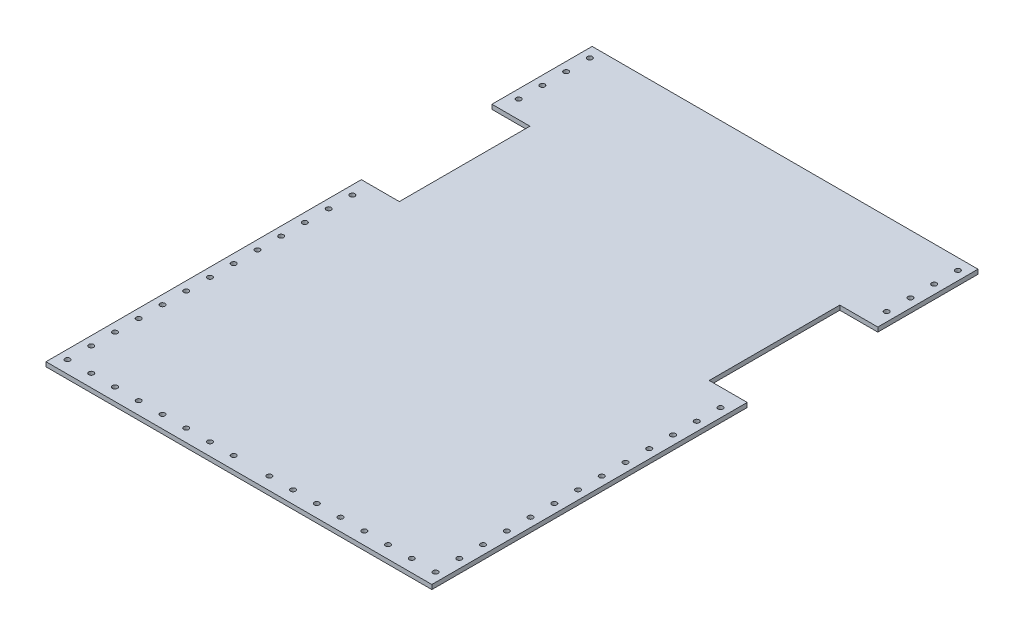
SolidWorks part; units mm, degrees
material "Teak"
ref_plane "Front Plane" through (0, 0, 0) normal (0, 0, 1) x (1, 0, 0)
ref_plane "Top Plane" through (0, 0, 0) normal (0, 1, 0) x (1, 0, 0)
ref_plane "Right Plane" through (0, 0, 0) normal (1, 0, 0) x (0, 0, -1)
sketch "Sketch1" plane through (0, 0, 0) normal (0, 1, 0) x (1, 0, 0)
  line L1 (0, 0) -> (412.75, 0)
  line L2 (0, 0) -> (0, 584.2)
  line L3 (0, 584.2) -> (412.75, 584.2)
  line L4 (412.75, 0) -> (412.75, 584.2)
  dimension "D1" = 584.2
  dimension "D2" = 412.75
extrude "Boss-Extrude1" add sketch "Sketch1" along normal blind 4.7625
sketch "Sketch2" plane through (0, 4.7625, 0) normal (0, 1, 0) x (1, 0, 0)
  line L0 (0, 584.2) -> (0, 0) construction
  line L1 (0, 477.012) -> (40.64, 477.012)
  line L2 (0, 477.012) -> (0, 337.312)
  line L3 (0, 337.312) -> (40.64, 337.312)
  line L4 (40.64, 477.012) -> (40.64, 337.312)
  line L5 (206.375, 0) -> (206.375, 59.5989)
  line L7 (0, 0) -> (412.75, 0) construction
  line L8 (372.11, 477.012) -> (372.11, 337.312)
  line L9 (412.75, 337.312) -> (372.11, 337.312)
  line L10 (412.75, 477.012) -> (412.75, 337.312)
  line L11 (412.75, 477.012) -> (372.11, 477.012)
  line M5 (0, 584.2) -> (0, 0)
  line M7 (412.75, 0) -> (412.75, 584.2)
  dimension "D1" = 139.7
  dimension "D2" = 40.64
extrude "Cut-Extrude1" cut sketch "Sketch2" against normal through all contours L4 L1 L3 M5 | L11 L8 L9 M7
sketch "Sketch3" plane through (0, 4.7625, 0) normal (0, 1, 0) x (1, 0, 0)
  line L0 (0, 337.312) -> (0, 0) construction
  line L1 (0, 0) -> (412.75, 0) construction
  circle A0 centre (9.525, 13.462) radius 2.667
  circle A2 centre (34.925, 13.462) radius 2.667
  circle A4 centre (60.325, 13.462) radius 2.667
  circle A6 centre (85.725, 13.462) radius 2.667
  circle A8 centre (111.125, 13.462) radius 2.667
  circle A10 centre (136.525, 13.462) radius 2.667
  circle A12 centre (161.925, 13.462) radius 2.667
  circle A14 centre (187.325, 13.462) radius 2.667
  circle A17 centre (225.425, 13.462) radius 2.667
  circle A19 centre (250.825, 13.462) radius 2.667
  circle A21 centre (276.225, 13.462) radius 2.667
  circle A23 centre (301.625, 13.462) radius 2.667
  circle A25 centre (327.025, 13.462) radius 2.667
  circle A27 centre (352.425, 13.462) radius 2.667
  circle A29 centre (377.825, 13.462) radius 2.667
  circle A31 centre (403.225, 13.462) radius 2.667
  circle A62 centre (403.225, 38.862) radius 2.667
  circle A93 centre (403.225, 64.262) radius 2.667
  circle A124 centre (403.225, 89.662) radius 2.667
  circle A155 centre (403.225, 115.062) radius 2.667
  circle A186 centre (403.225, 140.462) radius 2.667
  circle A217 centre (403.225, 165.862) radius 2.667
  circle A248 centre (403.225, 191.262) radius 2.667
  circle A279 centre (403.225, 216.662) radius 2.667
  circle A310 centre (403.225, 242.062) radius 2.667
  circle A341 centre (403.225, 267.462) radius 2.667
  circle A372 centre (403.225, 292.862) radius 2.667
  circle A403 centre (403.225, 318.262) radius 2.667
  circle A434 centre (403.225, 343.662) radius 2.667
  circle A465 centre (403.225, 369.062) radius 2.667
  circle A496 centre (403.225, 394.462) radius 2.667
  circle A527 centre (403.225, 419.862) radius 2.667
  circle A558 centre (403.225, 445.262) radius 2.667
  circle A589 centre (403.225, 470.662) radius 2.667
  circle A620 centre (403.225, 496.062) radius 2.667
  circle A651 centre (403.225, 521.462) radius 2.667
  circle A682 centre (403.225, 546.862) radius 2.667
  circle A713 centre (403.225, 572.262) radius 2.667
  circle A714 centre (9.525, 38.862) radius 2.667
  circle A715 centre (9.525, 64.262) radius 2.667
  circle A716 centre (9.525, 89.662) radius 2.667
  circle A717 centre (9.525, 115.062) radius 2.667
  circle A718 centre (9.525, 140.462) radius 2.667
  circle A719 centre (9.525, 165.862) radius 2.667
  circle A720 centre (9.525, 191.262) radius 2.667
  circle A721 centre (9.525, 216.662) radius 2.667
  circle A722 centre (9.525, 242.062) radius 2.667
  circle A723 centre (9.525, 267.462) radius 2.667
  circle A724 centre (9.525, 292.862) radius 2.667
  circle A725 centre (9.525, 318.262) radius 2.667
  circle A726 centre (9.525, 343.662) radius 2.667
  circle A727 centre (9.525, 369.062) radius 2.667
  circle A728 centre (9.525, 394.462) radius 2.667
  circle A729 centre (9.525, 419.862) radius 2.667
  circle A730 centre (9.525, 445.262) radius 2.667
  circle A731 centre (9.525, 470.662) radius 2.667
  circle A732 centre (9.525, 496.062) radius 2.667
  circle A733 centre (9.525, 521.462) radius 2.667
  circle A734 centre (9.525, 546.862) radius 2.667
  circle A735 centre (9.525, 572.262) radius 2.667
  circle A736 centre (34.925, 38.862) radius 2.667 [skipped]
  circle A737 centre (47.625, 38.862) radius 2.667 [skipped]
  circle A738 centre (60.325, 38.862) radius 2.667 [skipped]
  circle A739 centre (73.025, 38.862) radius 2.667 [skipped]
  circle A740 centre (85.725, 38.862) radius 2.667 [skipped]
  circle A741 centre (98.425, 38.862) radius 2.667 [skipped]
  circle A742 centre (111.125, 38.862) radius 2.667 [skipped]
  circle A743 centre (123.825, 38.862) radius 2.667 [skipped]
  circle A744 centre (136.525, 38.862) radius 2.667 [skipped]
  circle A745 centre (149.225, 38.862) radius 2.667 [skipped]
  circle A746 centre (161.925, 38.862) radius 2.667 [skipped]
  circle A747 centre (174.625, 38.862) radius 2.667 [skipped]
  circle A748 centre (187.325, 38.862) radius 2.667 [skipped]
  circle A749 centre (200.025, 38.862) radius 2.667 [skipped]
  circle A750 centre (212.725, 38.862) radius 2.667 [skipped]
  circle A751 centre (225.425, 38.862) radius 2.667 [skipped]
  circle A752 centre (238.125, 38.862) radius 2.667 [skipped]
  circle A753 centre (250.825, 38.862) radius 2.667 [skipped]
  circle A754 centre (263.525, 38.862) radius 2.667 [skipped]
  circle A755 centre (276.225, 38.862) radius 2.667 [skipped]
  circle A756 centre (288.925, 38.862) radius 2.667 [skipped]
  circle A757 centre (301.625, 38.862) radius 2.667 [skipped]
  circle A758 centre (314.325, 38.862) radius 2.667 [skipped]
  circle A759 centre (327.025, 38.862) radius 2.667 [skipped]
  circle A760 centre (339.725, 38.862) radius 2.667 [skipped]
  circle A761 centre (352.425, 38.862) radius 2.667 [skipped]
  circle A762 centre (365.125, 38.862) radius 2.667 [skipped]
  circle A763 centre (377.825, 38.862) radius 2.667 [skipped]
  circle A764 centre (390.525, 38.862) radius 2.667 [skipped]
  circle A765 centre (34.925, 64.262) radius 2.667 [skipped]
  circle A766 centre (47.625, 64.262) radius 2.667 [skipped]
  circle A767 centre (60.325, 64.262) radius 2.667 [skipped]
  circle A768 centre (73.025, 64.262) radius 2.667 [skipped]
  circle A769 centre (85.725, 64.262) radius 2.667 [skipped]
  circle A770 centre (98.425, 64.262) radius 2.667 [skipped]
  circle A771 centre (111.125, 64.262) radius 2.667 [skipped]
  circle A772 centre (123.825, 64.262) radius 2.667 [skipped]
  circle A773 centre (136.525, 64.262) radius 2.667 [skipped]
  circle A774 centre (149.225, 64.262) radius 2.667 [skipped]
  circle A775 centre (161.925, 64.262) radius 2.667 [skipped]
  circle A776 centre (174.625, 64.262) radius 2.667 [skipped]
  circle A777 centre (187.325, 64.262) radius 2.667 [skipped]
  circle A778 centre (200.025, 64.262) radius 2.667 [skipped]
  circle A779 centre (212.725, 64.262) radius 2.667 [skipped]
  circle A780 centre (225.425, 64.262) radius 2.667 [skipped]
  circle A781 centre (238.125, 64.262) radius 2.667 [skipped]
  circle A782 centre (250.825, 64.262) radius 2.667 [skipped]
  circle A783 centre (263.525, 64.262) radius 2.667 [skipped]
  circle A784 centre (276.225, 64.262) radius 2.667 [skipped]
  circle A785 centre (288.925, 64.262) radius 2.667 [skipped]
  circle A786 centre (301.625, 64.262) radius 2.667 [skipped]
  circle A787 centre (314.325, 64.262) radius 2.667 [skipped]
  circle A788 centre (327.025, 64.262) radius 2.667 [skipped]
  circle A789 centre (339.725, 64.262) radius 2.667 [skipped]
  circle A790 centre (352.425, 64.262) radius 2.667 [skipped]
  circle A791 centre (365.125, 64.262) radius 2.667 [skipped]
  circle A792 centre (377.825, 64.262) radius 2.667 [skipped]
  circle A793 centre (390.525, 64.262) radius 2.667 [skipped]
  circle A794 centre (34.925, 89.662) radius 2.667 [skipped]
  circle A795 centre (47.625, 89.662) radius 2.667 [skipped]
  circle A796 centre (60.325, 89.662) radius 2.667 [skipped]
  circle A797 centre (73.025, 89.662) radius 2.667 [skipped]
  circle A798 centre (85.725, 89.662) radius 2.667 [skipped]
  circle A799 centre (98.425, 89.662) radius 2.667 [skipped]
  circle A800 centre (111.125, 89.662) radius 2.667 [skipped]
  circle A801 centre (123.825, 89.662) radius 2.667 [skipped]
  circle A802 centre (136.525, 89.662) radius 2.667 [skipped]
  circle A803 centre (149.225, 89.662) radius 2.667 [skipped]
  circle A804 centre (161.925, 89.662) radius 2.667 [skipped]
  circle A805 centre (174.625, 89.662) radius 2.667 [skipped]
  circle A806 centre (187.325, 89.662) radius 2.667 [skipped]
  circle A807 centre (200.025, 89.662) radius 2.667 [skipped]
  circle A808 centre (212.725, 89.662) radius 2.667 [skipped]
  circle A809 centre (225.425, 89.662) radius 2.667 [skipped]
  circle A810 centre (238.125, 89.662) radius 2.667 [skipped]
  circle A811 centre (250.825, 89.662) radius 2.667 [skipped]
  circle A812 centre (263.525, 89.662) radius 2.667 [skipped]
  circle A813 centre (276.225, 89.662) radius 2.667 [skipped]
  circle A814 centre (288.925, 89.662) radius 2.667 [skipped]
  circle A815 centre (301.625, 89.662) radius 2.667 [skipped]
  circle A816 centre (314.325, 89.662) radius 2.667 [skipped]
  circle A817 centre (327.025, 89.662) radius 2.667 [skipped]
  circle A818 centre (339.725, 89.662) radius 2.667 [skipped]
  circle A819 centre (352.425, 89.662) radius 2.667 [skipped]
  circle A820 centre (365.125, 89.662) radius 2.667 [skipped]
  circle A821 centre (377.825, 89.662) radius 2.667 [skipped]
  circle A822 centre (390.525, 89.662) radius 2.667 [skipped]
  circle A823 centre (34.925, 115.062) radius 2.667 [skipped]
  circle A824 centre (47.625, 115.062) radius 2.667 [skipped]
  circle A825 centre (60.325, 115.062) radius 2.667 [skipped]
  circle A826 centre (73.025, 115.062) radius 2.667 [skipped]
  circle A827 centre (85.725, 115.062) radius 2.667 [skipped]
  circle A828 centre (98.425, 115.062) radius 2.667 [skipped]
  circle A829 centre (111.125, 115.062) radius 2.667 [skipped]
  circle A830 centre (123.825, 115.062) radius 2.667 [skipped]
  circle A831 centre (136.525, 115.062) radius 2.667 [skipped]
  circle A832 centre (149.225, 115.062) radius 2.667 [skipped]
  circle A833 centre (161.925, 115.062) radius 2.667 [skipped]
  circle A834 centre (174.625, 115.062) radius 2.667 [skipped]
  circle A835 centre (187.325, 115.062) radius 2.667 [skipped]
  circle A836 centre (200.025, 115.062) radius 2.667 [skipped]
  circle A837 centre (212.725, 115.062) radius 2.667 [skipped]
  circle A838 centre (225.425, 115.062) radius 2.667 [skipped]
  circle A839 centre (238.125, 115.062) radius 2.667 [skipped]
  circle A840 centre (250.825, 115.062) radius 2.667 [skipped]
  circle A841 centre (263.525, 115.062) radius 2.667 [skipped]
  circle A842 centre (276.225, 115.062) radius 2.667 [skipped]
  circle A843 centre (288.925, 115.062) radius 2.667 [skipped]
  circle A844 centre (301.625, 115.062) radius 2.667 [skipped]
  circle A845 centre (314.325, 115.062) radius 2.667 [skipped]
  circle A846 centre (327.025, 115.062) radius 2.667 [skipped]
  circle A847 centre (339.725, 115.062) radius 2.667 [skipped]
  circle A848 centre (352.425, 115.062) radius 2.667 [skipped]
  circle A849 centre (365.125, 115.062) radius 2.667 [skipped]
  circle A850 centre (377.825, 115.062) radius 2.667 [skipped]
  circle A851 centre (390.525, 115.062) radius 2.667 [skipped]
  circle A852 centre (34.925, 140.462) radius 2.667 [skipped]
  circle A853 centre (47.625, 140.462) radius 2.667 [skipped]
  circle A854 centre (60.325, 140.462) radius 2.667 [skipped]
  circle A855 centre (73.025, 140.462) radius 2.667 [skipped]
  circle A856 centre (85.725, 140.462) radius 2.667 [skipped]
  circle A857 centre (98.425, 140.462) radius 2.667 [skipped]
  circle A858 centre (111.125, 140.462) radius 2.667 [skipped]
  circle A859 centre (123.825, 140.462) radius 2.667 [skipped]
  circle A860 centre (136.525, 140.462) radius 2.667 [skipped]
  circle A861 centre (149.225, 140.462) radius 2.667 [skipped]
  circle A862 centre (161.925, 140.462) radius 2.667 [skipped]
  circle A863 centre (174.625, 140.462) radius 2.667 [skipped]
  circle A864 centre (187.325, 140.462) radius 2.667 [skipped]
  circle A865 centre (200.025, 140.462) radius 2.667 [skipped]
  circle A866 centre (212.725, 140.462) radius 2.667 [skipped]
  circle A867 centre (225.425, 140.462) radius 2.667 [skipped]
  circle A868 centre (238.125, 140.462) radius 2.667 [skipped]
  circle A869 centre (250.825, 140.462) radius 2.667 [skipped]
  circle A870 centre (263.525, 140.462) radius 2.667 [skipped]
  circle A871 centre (276.225, 140.462) radius 2.667 [skipped]
  circle A872 centre (288.925, 140.462) radius 2.667 [skipped]
  circle A873 centre (301.625, 140.462) radius 2.667 [skipped]
  circle A874 centre (314.325, 140.462) radius 2.667 [skipped]
  circle A875 centre (327.025, 140.462) radius 2.667 [skipped]
  circle A876 centre (339.725, 140.462) radius 2.667 [skipped]
  circle A877 centre (352.425, 140.462) radius 2.667 [skipped]
  circle A878 centre (365.125, 140.462) radius 2.667 [skipped]
  circle A879 centre (377.825, 140.462) radius 2.667 [skipped]
  circle A880 centre (390.525, 140.462) radius 2.667 [skipped]
  circle A881 centre (34.925, 165.862) radius 2.667 [skipped]
  circle A882 centre (47.625, 165.862) radius 2.667 [skipped]
  circle A883 centre (60.325, 165.862) radius 2.667 [skipped]
  circle A884 centre (73.025, 165.862) radius 2.667 [skipped]
  circle A885 centre (85.725, 165.862) radius 2.667 [skipped]
  circle A886 centre (98.425, 165.862) radius 2.667 [skipped]
  circle A887 centre (111.125, 165.862) radius 2.667 [skipped]
  circle A888 centre (123.825, 165.862) radius 2.667 [skipped]
  circle A889 centre (136.525, 165.862) radius 2.667 [skipped]
  circle A890 centre (149.225, 165.862) radius 2.667 [skipped]
  circle A891 centre (161.925, 165.862) radius 2.667 [skipped]
  circle A892 centre (174.625, 165.862) radius 2.667 [skipped]
  circle A893 centre (187.325, 165.862) radius 2.667 [skipped]
  circle A894 centre (200.025, 165.862) radius 2.667 [skipped]
  circle A895 centre (212.725, 165.862) radius 2.667 [skipped]
  circle A896 centre (225.425, 165.862) radius 2.667 [skipped]
  circle A897 centre (238.125, 165.862) radius 2.667 [skipped]
  circle A898 centre (250.825, 165.862) radius 2.667 [skipped]
  circle A899 centre (263.525, 165.862) radius 2.667 [skipped]
  circle A900 centre (276.225, 165.862) radius 2.667 [skipped]
  circle A901 centre (288.925, 165.862) radius 2.667 [skipped]
  circle A902 centre (301.625, 165.862) radius 2.667 [skipped]
  circle A903 centre (314.325, 165.862) radius 2.667 [skipped]
  circle A904 centre (327.025, 165.862) radius 2.667 [skipped]
  circle A905 centre (339.725, 165.862) radius 2.667 [skipped]
  circle A906 centre (352.425, 165.862) radius 2.667 [skipped]
  circle A907 centre (365.125, 165.862) radius 2.667 [skipped]
  circle A908 centre (377.825, 165.862) radius 2.667 [skipped]
  circle A909 centre (390.525, 165.862) radius 2.667 [skipped]
  circle A910 centre (34.925, 191.262) radius 2.667 [skipped]
  circle A911 centre (47.625, 191.262) radius 2.667 [skipped]
  circle A912 centre (60.325, 191.262) radius 2.667 [skipped]
  circle A913 centre (73.025, 191.262) radius 2.667 [skipped]
  circle A914 centre (85.725, 191.262) radius 2.667 [skipped]
  circle A915 centre (98.425, 191.262) radius 2.667 [skipped]
  circle A916 centre (111.125, 191.262) radius 2.667 [skipped]
  circle A917 centre (123.825, 191.262) radius 2.667 [skipped]
  circle A918 centre (136.525, 191.262) radius 2.667 [skipped]
  circle A919 centre (149.225, 191.262) radius 2.667 [skipped]
  circle A920 centre (161.925, 191.262) radius 2.667 [skipped]
  circle A921 centre (174.625, 191.262) radius 2.667 [skipped]
  circle A922 centre (187.325, 191.262) radius 2.667 [skipped]
  circle A923 centre (200.025, 191.262) radius 2.667 [skipped]
  circle A924 centre (212.725, 191.262) radius 2.667 [skipped]
  circle A925 centre (225.425, 191.262) radius 2.667 [skipped]
  circle A926 centre (238.125, 191.262) radius 2.667 [skipped]
  circle A927 centre (250.825, 191.262) radius 2.667 [skipped]
  circle A928 centre (263.525, 191.262) radius 2.667 [skipped]
  circle A929 centre (276.225, 191.262) radius 2.667 [skipped]
  circle A930 centre (288.925, 191.262) radius 2.667 [skipped]
  circle A931 centre (301.625, 191.262) radius 2.667 [skipped]
  circle A932 centre (314.325, 191.262) radius 2.667 [skipped]
  circle A933 centre (327.025, 191.262) radius 2.667 [skipped]
  circle A934 centre (339.725, 191.262) radius 2.667 [skipped]
  circle A935 centre (352.425, 191.262) radius 2.667 [skipped]
  circle A936 centre (365.125, 191.262) radius 2.667 [skipped]
  circle A937 centre (377.825, 191.262) radius 2.667 [skipped]
  circle A938 centre (390.525, 191.262) radius 2.667 [skipped]
  circle A939 centre (34.925, 216.662) radius 2.667 [skipped]
  circle A940 centre (47.625, 216.662) radius 2.667 [skipped]
  circle A941 centre (60.325, 216.662) radius 2.667 [skipped]
  circle A942 centre (73.025, 216.662) radius 2.667 [skipped]
  circle A943 centre (85.725, 216.662) radius 2.667 [skipped]
  circle A944 centre (98.425, 216.662) radius 2.667 [skipped]
  circle A945 centre (111.125, 216.662) radius 2.667 [skipped]
  circle A946 centre (123.825, 216.662) radius 2.667 [skipped]
  circle A947 centre (136.525, 216.662) radius 2.667 [skipped]
  circle A948 centre (149.225, 216.662) radius 2.667 [skipped]
  circle A949 centre (161.925, 216.662) radius 2.667 [skipped]
  circle A950 centre (174.625, 216.662) radius 2.667 [skipped]
  circle A951 centre (187.325, 216.662) radius 2.667 [skipped]
  circle A952 centre (200.025, 216.662) radius 2.667 [skipped]
  circle A953 centre (212.725, 216.662) radius 2.667 [skipped]
  circle A954 centre (225.425, 216.662) radius 2.667 [skipped]
  circle A955 centre (238.125, 216.662) radius 2.667 [skipped]
  circle A956 centre (250.825, 216.662) radius 2.667 [skipped]
  circle A957 centre (263.525, 216.662) radius 2.667 [skipped]
  circle A958 centre (276.225, 216.662) radius 2.667 [skipped]
  circle A959 centre (288.925, 216.662) radius 2.667 [skipped]
  circle A960 centre (301.625, 216.662) radius 2.667 [skipped]
  circle A961 centre (314.325, 216.662) radius 2.667 [skipped]
  circle A962 centre (327.025, 216.662) radius 2.667 [skipped]
  circle A963 centre (339.725, 216.662) radius 2.667 [skipped]
  circle A964 centre (352.425, 216.662) radius 2.667 [skipped]
  circle A965 centre (365.125, 216.662) radius 2.667 [skipped]
  circle A966 centre (377.825, 216.662) radius 2.667 [skipped]
  circle A967 centre (390.525, 216.662) radius 2.667 [skipped]
  circle A968 centre (34.925, 242.062) radius 2.667 [skipped]
  circle A969 centre (47.625, 242.062) radius 2.667 [skipped]
  circle A970 centre (60.325, 242.062) radius 2.667 [skipped]
  circle A971 centre (73.025, 242.062) radius 2.667 [skipped]
  circle A972 centre (85.725, 242.062) radius 2.667 [skipped]
  circle A973 centre (98.425, 242.062) radius 2.667 [skipped]
  circle A974 centre (111.125, 242.062) radius 2.667 [skipped]
  circle A975 centre (123.825, 242.062) radius 2.667 [skipped]
  circle A976 centre (136.525, 242.062) radius 2.667 [skipped]
  circle A977 centre (149.225, 242.062) radius 2.667 [skipped]
  circle A978 centre (161.925, 242.062) radius 2.667 [skipped]
  circle A979 centre (174.625, 242.062) radius 2.667 [skipped]
  circle A980 centre (187.325, 242.062) radius 2.667 [skipped]
  circle A981 centre (200.025, 242.062) radius 2.667 [skipped]
  circle A982 centre (212.725, 242.062) radius 2.667 [skipped]
  circle A983 centre (225.425, 242.062) radius 2.667 [skipped]
  circle A984 centre (238.125, 242.062) radius 2.667 [skipped]
  circle A985 centre (250.825, 242.062) radius 2.667 [skipped]
  circle A986 centre (263.525, 242.062) radius 2.667 [skipped]
  circle A987 centre (276.225, 242.062) radius 2.667 [skipped]
  circle A988 centre (288.925, 242.062) radius 2.667 [skipped]
  circle A989 centre (301.625, 242.062) radius 2.667 [skipped]
  circle A990 centre (314.325, 242.062) radius 2.667 [skipped]
  circle A991 centre (327.025, 242.062) radius 2.667 [skipped]
  circle A992 centre (339.725, 242.062) radius 2.667 [skipped]
  circle A993 centre (352.425, 242.062) radius 2.667 [skipped]
  circle A994 centre (365.125, 242.062) radius 2.667 [skipped]
  circle A995 centre (377.825, 242.062) radius 2.667 [skipped]
  circle A996 centre (390.525, 242.062) radius 2.667 [skipped]
  circle A997 centre (34.925, 267.462) radius 2.667 [skipped]
  circle A998 centre (47.625, 267.462) radius 2.667 [skipped]
  circle A999 centre (60.325, 267.462) radius 2.667 [skipped]
  circle A1000 centre (73.025, 267.462) radius 2.667 [skipped]
  circle A1001 centre (85.725, 267.462) radius 2.667 [skipped]
  circle A1002 centre (98.425, 267.462) radius 2.667 [skipped]
  circle A1003 centre (111.125, 267.462) radius 2.667 [skipped]
  circle A1004 centre (123.825, 267.462) radius 2.667 [skipped]
  circle A1005 centre (136.525, 267.462) radius 2.667 [skipped]
  circle A1006 centre (149.225, 267.462) radius 2.667 [skipped]
  circle A1007 centre (161.925, 267.462) radius 2.667 [skipped]
  circle A1008 centre (174.625, 267.462) radius 2.667 [skipped]
  circle A1009 centre (187.325, 267.462) radius 2.667 [skipped]
  circle A1010 centre (200.025, 267.462) radius 2.667 [skipped]
  circle A1011 centre (212.725, 267.462) radius 2.667 [skipped]
  circle A1012 centre (225.425, 267.462) radius 2.667 [skipped]
  circle A1013 centre (238.125, 267.462) radius 2.667 [skipped]
  circle A1014 centre (250.825, 267.462) radius 2.667 [skipped]
  circle A1015 centre (263.525, 267.462) radius 2.667 [skipped]
  circle A1016 centre (276.225, 267.462) radius 2.667 [skipped]
  circle A1017 centre (288.925, 267.462) radius 2.667 [skipped]
  circle A1018 centre (301.625, 267.462) radius 2.667 [skipped]
  circle A1019 centre (314.325, 267.462) radius 2.667 [skipped]
  circle A1020 centre (327.025, 267.462) radius 2.667 [skipped]
  circle A1021 centre (339.725, 267.462) radius 2.667 [skipped]
  circle A1022 centre (352.425, 267.462) radius 2.667 [skipped]
  circle A1023 centre (365.125, 267.462) radius 2.667 [skipped]
  circle A1024 centre (377.825, 267.462) radius 2.667 [skipped]
  circle A1025 centre (390.525, 267.462) radius 2.667 [skipped]
  circle A1026 centre (34.925, 292.862) radius 2.667 [skipped]
  circle A1027 centre (47.625, 292.862) radius 2.667 [skipped]
  circle A1028 centre (60.325, 292.862) radius 2.667 [skipped]
  circle A1029 centre (73.025, 292.862) radius 2.667 [skipped]
  circle A1030 centre (85.725, 292.862) radius 2.667 [skipped]
  circle A1031 centre (98.425, 292.862) radius 2.667 [skipped]
  circle A1032 centre (111.125, 292.862) radius 2.667 [skipped]
  circle A1033 centre (123.825, 292.862) radius 2.667 [skipped]
  circle A1034 centre (136.525, 292.862) radius 2.667 [skipped]
  circle A1035 centre (149.225, 292.862) radius 2.667 [skipped]
  circle A1036 centre (161.925, 292.862) radius 2.667 [skipped]
  circle A1037 centre (174.625, 292.862) radius 2.667 [skipped]
  circle A1038 centre (187.325, 292.862) radius 2.667 [skipped]
  circle A1039 centre (200.025, 292.862) radius 2.667 [skipped]
  circle A1040 centre (212.725, 292.862) radius 2.667 [skipped]
  circle A1041 centre (225.425, 292.862) radius 2.667 [skipped]
  circle A1042 centre (238.125, 292.862) radius 2.667 [skipped]
  circle A1043 centre (250.825, 292.862) radius 2.667 [skipped]
  circle A1044 centre (263.525, 292.862) radius 2.667 [skipped]
  circle A1045 centre (276.225, 292.862) radius 2.667 [skipped]
  circle A1046 centre (288.925, 292.862) radius 2.667 [skipped]
  circle A1047 centre (301.625, 292.862) radius 2.667 [skipped]
  circle A1048 centre (314.325, 292.862) radius 2.667 [skipped]
  circle A1049 centre (327.025, 292.862) radius 2.667 [skipped]
  circle A1050 centre (339.725, 292.862) radius 2.667 [skipped]
  circle A1051 centre (352.425, 292.862) radius 2.667 [skipped]
  circle A1052 centre (365.125, 292.862) radius 2.667 [skipped]
  circle A1053 centre (377.825, 292.862) radius 2.667 [skipped]
  circle A1054 centre (390.525, 292.862) radius 2.667 [skipped]
  circle A1055 centre (34.925, 318.262) radius 2.667 [skipped]
  circle A1056 centre (47.625, 318.262) radius 2.667 [skipped]
  circle A1057 centre (60.325, 318.262) radius 2.667 [skipped]
  circle A1058 centre (73.025, 318.262) radius 2.667 [skipped]
  circle A1059 centre (85.725, 318.262) radius 2.667 [skipped]
  circle A1060 centre (98.425, 318.262) radius 2.667 [skipped]
  circle A1061 centre (111.125, 318.262) radius 2.667 [skipped]
  circle A1062 centre (123.825, 318.262) radius 2.667 [skipped]
  circle A1063 centre (136.525, 318.262) radius 2.667 [skipped]
  circle A1064 centre (149.225, 318.262) radius 2.667 [skipped]
  circle A1065 centre (161.925, 318.262) radius 2.667 [skipped]
  circle A1066 centre (174.625, 318.262) radius 2.667 [skipped]
  circle A1067 centre (187.325, 318.262) radius 2.667 [skipped]
  circle A1068 centre (200.025, 318.262) radius 2.667 [skipped]
  circle A1069 centre (212.725, 318.262) radius 2.667 [skipped]
  circle A1070 centre (225.425, 318.262) radius 2.667 [skipped]
  circle A1071 centre (238.125, 318.262) radius 2.667 [skipped]
  circle A1072 centre (250.825, 318.262) radius 2.667 [skipped]
  circle A1073 centre (263.525, 318.262) radius 2.667 [skipped]
  circle A1074 centre (276.225, 318.262) radius 2.667 [skipped]
  circle A1075 centre (288.925, 318.262) radius 2.667 [skipped]
  circle A1076 centre (301.625, 318.262) radius 2.667 [skipped]
  circle A1077 centre (314.325, 318.262) radius 2.667 [skipped]
  circle A1078 centre (327.025, 318.262) radius 2.667 [skipped]
  circle A1079 centre (339.725, 318.262) radius 2.667 [skipped]
  circle A1080 centre (352.425, 318.262) radius 2.667 [skipped]
  circle A1081 centre (365.125, 318.262) radius 2.667 [skipped]
  circle A1082 centre (377.825, 318.262) radius 2.667 [skipped]
  circle A1083 centre (390.525, 318.262) radius 2.667 [skipped]
  circle A1084 centre (34.925, 343.662) radius 2.667 [skipped]
  circle A1085 centre (47.625, 343.662) radius 2.667 [skipped]
  circle A1086 centre (60.325, 343.662) radius 2.667 [skipped]
  circle A1087 centre (73.025, 343.662) radius 2.667 [skipped]
  circle A1088 centre (85.725, 343.662) radius 2.667 [skipped]
  circle A1089 centre (98.425, 343.662) radius 2.667 [skipped]
  circle A1090 centre (111.125, 343.662) radius 2.667 [skipped]
  circle A1091 centre (123.825, 343.662) radius 2.667 [skipped]
  circle A1092 centre (136.525, 343.662) radius 2.667 [skipped]
  circle A1093 centre (149.225, 343.662) radius 2.667 [skipped]
  circle A1094 centre (161.925, 343.662) radius 2.667 [skipped]
  circle A1095 centre (174.625, 343.662) radius 2.667 [skipped]
  circle A1096 centre (187.325, 343.662) radius 2.667 [skipped]
  circle A1097 centre (200.025, 343.662) radius 2.667 [skipped]
  circle A1098 centre (212.725, 343.662) radius 2.667 [skipped]
  circle A1099 centre (225.425, 343.662) radius 2.667 [skipped]
  circle A1100 centre (238.125, 343.662) radius 2.667 [skipped]
  circle A1101 centre (250.825, 343.662) radius 2.667 [skipped]
  circle A1102 centre (263.525, 343.662) radius 2.667 [skipped]
  circle A1103 centre (276.225, 343.662) radius 2.667 [skipped]
  circle A1104 centre (288.925, 343.662) radius 2.667 [skipped]
  circle A1105 centre (301.625, 343.662) radius 2.667 [skipped]
  circle A1106 centre (314.325, 343.662) radius 2.667 [skipped]
  circle A1107 centre (327.025, 343.662) radius 2.667 [skipped]
  circle A1108 centre (339.725, 343.662) radius 2.667 [skipped]
  circle A1109 centre (352.425, 343.662) radius 2.667 [skipped]
  circle A1110 centre (365.125, 343.662) radius 2.667 [skipped]
  circle A1111 centre (377.825, 343.662) radius 2.667 [skipped]
  circle A1112 centre (390.525, 343.662) radius 2.667 [skipped]
  circle A1113 centre (34.925, 369.062) radius 2.667 [skipped]
  circle A1114 centre (47.625, 369.062) radius 2.667 [skipped]
  circle A1115 centre (60.325, 369.062) radius 2.667 [skipped]
  circle A1116 centre (73.025, 369.062) radius 2.667 [skipped]
  circle A1117 centre (85.725, 369.062) radius 2.667 [skipped]
  circle A1118 centre (98.425, 369.062) radius 2.667 [skipped]
  circle A1119 centre (111.125, 369.062) radius 2.667 [skipped]
  circle A1120 centre (123.825, 369.062) radius 2.667 [skipped]
  circle A1121 centre (136.525, 369.062) radius 2.667 [skipped]
  circle A1122 centre (149.225, 369.062) radius 2.667 [skipped]
  circle A1123 centre (161.925, 369.062) radius 2.667 [skipped]
  circle A1124 centre (174.625, 369.062) radius 2.667 [skipped]
  circle A1125 centre (187.325, 369.062) radius 2.667 [skipped]
  circle A1126 centre (200.025, 369.062) radius 2.667 [skipped]
  circle A1127 centre (212.725, 369.062) radius 2.667 [skipped]
  circle A1128 centre (225.425, 369.062) radius 2.667 [skipped]
  circle A1129 centre (238.125, 369.062) radius 2.667 [skipped]
  circle A1130 centre (250.825, 369.062) radius 2.667 [skipped]
  circle A1131 centre (263.525, 369.062) radius 2.667 [skipped]
  circle A1132 centre (276.225, 369.062) radius 2.667 [skipped]
  circle A1133 centre (288.925, 369.062) radius 2.667 [skipped]
  circle A1134 centre (301.625, 369.062) radius 2.667 [skipped]
  circle A1135 centre (314.325, 369.062) radius 2.667 [skipped]
  circle A1136 centre (327.025, 369.062) radius 2.667 [skipped]
  circle A1137 centre (339.725, 369.062) radius 2.667 [skipped]
  circle A1138 centre (352.425, 369.062) radius 2.667 [skipped]
  circle A1139 centre (365.125, 369.062) radius 2.667 [skipped]
  circle A1140 centre (377.825, 369.062) radius 2.667 [skipped]
  circle A1141 centre (390.525, 369.062) radius 2.667 [skipped]
  circle A1142 centre (34.925, 394.462) radius 2.667 [skipped]
  circle A1143 centre (47.625, 394.462) radius 2.667 [skipped]
  circle A1144 centre (60.325, 394.462) radius 2.667 [skipped]
  circle A1145 centre (73.025, 394.462) radius 2.667 [skipped]
  circle A1146 centre (85.725, 394.462) radius 2.667 [skipped]
  circle A1147 centre (98.425, 394.462) radius 2.667 [skipped]
  circle A1148 centre (111.125, 394.462) radius 2.667 [skipped]
  circle A1149 centre (123.825, 394.462) radius 2.667 [skipped]
  circle A1150 centre (136.525, 394.462) radius 2.667 [skipped]
  circle A1151 centre (149.225, 394.462) radius 2.667 [skipped]
  circle A1152 centre (161.925, 394.462) radius 2.667 [skipped]
  circle A1153 centre (174.625, 394.462) radius 2.667 [skipped]
  circle A1154 centre (187.325, 394.462) radius 2.667 [skipped]
  circle A1155 centre (200.025, 394.462) radius 2.667 [skipped]
  circle A1156 centre (212.725, 394.462) radius 2.667 [skipped]
  circle A1157 centre (225.425, 394.462) radius 2.667 [skipped]
  circle A1158 centre (238.125, 394.462) radius 2.667 [skipped]
  circle A1159 centre (250.825, 394.462) radius 2.667 [skipped]
  circle A1160 centre (263.525, 394.462) radius 2.667 [skipped]
  circle A1161 centre (276.225, 394.462) radius 2.667 [skipped]
  circle A1162 centre (288.925, 394.462) radius 2.667 [skipped]
  circle A1163 centre (301.625, 394.462) radius 2.667 [skipped]
  circle A1164 centre (314.325, 394.462) radius 2.667 [skipped]
  circle A1165 centre (327.025, 394.462) radius 2.667 [skipped]
  circle A1166 centre (339.725, 394.462) radius 2.667 [skipped]
  circle A1167 centre (352.425, 394.462) radius 2.667 [skipped]
  circle A1168 centre (365.125, 394.462) radius 2.667 [skipped]
  circle A1169 centre (377.825, 394.462) radius 2.667 [skipped]
  circle A1170 centre (390.525, 394.462) radius 2.667 [skipped]
  circle A1171 centre (34.925, 419.862) radius 2.667 [skipped]
  circle A1172 centre (47.625, 419.862) radius 2.667 [skipped]
  circle A1173 centre (60.325, 419.862) radius 2.667 [skipped]
  circle A1174 centre (73.025, 419.862) radius 2.667 [skipped]
  circle A1175 centre (85.725, 419.862) radius 2.667 [skipped]
  circle A1176 centre (98.425, 419.862) radius 2.667 [skipped]
  circle A1177 centre (111.125, 419.862) radius 2.667 [skipped]
  circle A1178 centre (123.825, 419.862) radius 2.667 [skipped]
  circle A1179 centre (136.525, 419.862) radius 2.667 [skipped]
  circle A1180 centre (149.225, 419.862) radius 2.667 [skipped]
  circle A1181 centre (161.925, 419.862) radius 2.667 [skipped]
  circle A1182 centre (174.625, 419.862) radius 2.667 [skipped]
  circle A1183 centre (187.325, 419.862) radius 2.667 [skipped]
  circle A1184 centre (200.025, 419.862) radius 2.667 [skipped]
  circle A1185 centre (212.725, 419.862) radius 2.667 [skipped]
  circle A1186 centre (225.425, 419.862) radius 2.667 [skipped]
  circle A1187 centre (238.125, 419.862) radius 2.667 [skipped]
  circle A1188 centre (250.825, 419.862) radius 2.667 [skipped]
  circle A1189 centre (263.525, 419.862) radius 2.667 [skipped]
  circle A1190 centre (276.225, 419.862) radius 2.667 [skipped]
  circle A1191 centre (288.925, 419.862) radius 2.667 [skipped]
  circle A1192 centre (301.625, 419.862) radius 2.667 [skipped]
  circle A1193 centre (314.325, 419.862) radius 2.667 [skipped]
  circle A1194 centre (327.025, 419.862) radius 2.667 [skipped]
  circle A1195 centre (339.725, 419.862) radius 2.667 [skipped]
  circle A1196 centre (352.425, 419.862) radius 2.667 [skipped]
  circle A1197 centre (365.125, 419.862) radius 2.667 [skipped]
  circle A1198 centre (377.825, 419.862) radius 2.667 [skipped]
  circle A1199 centre (390.525, 419.862) radius 2.667 [skipped]
  circle A1200 centre (34.925, 445.262) radius 2.667 [skipped]
  circle A1201 centre (47.625, 445.262) radius 2.667 [skipped]
  circle A1202 centre (60.325, 445.262) radius 2.667 [skipped]
  circle A1203 centre (73.025, 445.262) radius 2.667 [skipped]
  circle A1204 centre (85.725, 445.262) radius 2.667 [skipped]
  circle A1205 centre (98.425, 445.262) radius 2.667 [skipped]
  circle A1206 centre (111.125, 445.262) radius 2.667 [skipped]
  circle A1207 centre (123.825, 445.262) radius 2.667 [skipped]
  circle A1208 centre (136.525, 445.262) radius 2.667 [skipped]
  circle A1209 centre (149.225, 445.262) radius 2.667 [skipped]
  circle A1210 centre (161.925, 445.262) radius 2.667 [skipped]
  circle A1211 centre (174.625, 445.262) radius 2.667 [skipped]
  circle A1212 centre (187.325, 445.262) radius 2.667 [skipped]
  circle A1213 centre (200.025, 445.262) radius 2.667 [skipped]
  circle A1214 centre (212.725, 445.262) radius 2.667 [skipped]
  circle A1215 centre (225.425, 445.262) radius 2.667 [skipped]
  circle A1216 centre (238.125, 445.262) radius 2.667 [skipped]
  circle A1217 centre (250.825, 445.262) radius 2.667 [skipped]
  circle A1218 centre (263.525, 445.262) radius 2.667 [skipped]
  circle A1219 centre (276.225, 445.262) radius 2.667 [skipped]
  circle A1220 centre (288.925, 445.262) radius 2.667 [skipped]
  circle A1221 centre (301.625, 445.262) radius 2.667 [skipped]
  circle A1222 centre (314.325, 445.262) radius 2.667 [skipped]
  circle A1223 centre (327.025, 445.262) radius 2.667 [skipped]
  circle A1224 centre (339.725, 445.262) radius 2.667 [skipped]
  circle A1225 centre (352.425, 445.262) radius 2.667 [skipped]
  circle A1226 centre (365.125, 445.262) radius 2.667 [skipped]
  circle A1227 centre (377.825, 445.262) radius 2.667 [skipped]
  circle A1228 centre (390.525, 445.262) radius 2.667 [skipped]
  circle A1229 centre (34.925, 470.662) radius 2.667 [skipped]
  circle A1230 centre (47.625, 470.662) radius 2.667 [skipped]
  circle A1231 centre (60.325, 470.662) radius 2.667 [skipped]
  circle A1232 centre (73.025, 470.662) radius 2.667 [skipped]
  circle A1233 centre (85.725, 470.662) radius 2.667 [skipped]
  circle A1234 centre (98.425, 470.662) radius 2.667 [skipped]
  circle A1235 centre (111.125, 470.662) radius 2.667 [skipped]
  circle A1236 centre (123.825, 470.662) radius 2.667 [skipped]
  circle A1237 centre (136.525, 470.662) radius 2.667 [skipped]
  circle A1238 centre (149.225, 470.662) radius 2.667 [skipped]
  circle A1239 centre (161.925, 470.662) radius 2.667 [skipped]
  circle A1240 centre (174.625, 470.662) radius 2.667 [skipped]
  circle A1241 centre (187.325, 470.662) radius 2.667 [skipped]
  circle A1242 centre (200.025, 470.662) radius 2.667 [skipped]
  circle A1243 centre (212.725, 470.662) radius 2.667 [skipped]
  circle A1244 centre (225.425, 470.662) radius 2.667 [skipped]
  circle A1245 centre (238.125, 470.662) radius 2.667 [skipped]
  circle A1246 centre (250.825, 470.662) radius 2.667 [skipped]
  circle A1247 centre (263.525, 470.662) radius 2.667 [skipped]
  circle A1248 centre (276.225, 470.662) radius 2.667 [skipped]
  circle A1249 centre (288.925, 470.662) radius 2.667 [skipped]
  circle A1250 centre (301.625, 470.662) radius 2.667 [skipped]
  circle A1251 centre (314.325, 470.662) radius 2.667 [skipped]
  circle A1252 centre (327.025, 470.662) radius 2.667 [skipped]
  circle A1253 centre (339.725, 470.662) radius 2.667 [skipped]
  circle A1254 centre (352.425, 470.662) radius 2.667 [skipped]
  circle A1255 centre (365.125, 470.662) radius 2.667 [skipped]
  circle A1256 centre (377.825, 470.662) radius 2.667 [skipped]
  circle A1257 centre (390.525, 470.662) radius 2.667 [skipped]
  circle A1258 centre (34.925, 496.062) radius 2.667 [skipped]
  circle A1259 centre (47.625, 496.062) radius 2.667 [skipped]
  circle A1260 centre (60.325, 496.062) radius 2.667 [skipped]
  circle A1261 centre (73.025, 496.062) radius 2.667 [skipped]
  circle A1262 centre (85.725, 496.062) radius 2.667 [skipped]
  circle A1263 centre (98.425, 496.062) radius 2.667 [skipped]
  circle A1264 centre (111.125, 496.062) radius 2.667 [skipped]
  circle A1265 centre (123.825, 496.062) radius 2.667 [skipped]
  circle A1266 centre (136.525, 496.062) radius 2.667 [skipped]
  circle A1267 centre (149.225, 496.062) radius 2.667 [skipped]
  circle A1268 centre (161.925, 496.062) radius 2.667 [skipped]
  circle A1269 centre (174.625, 496.062) radius 2.667 [skipped]
  circle A1270 centre (187.325, 496.062) radius 2.667 [skipped]
  circle A1271 centre (200.025, 496.062) radius 2.667 [skipped]
  circle A1272 centre (212.725, 496.062) radius 2.667 [skipped]
  circle A1273 centre (225.425, 496.062) radius 2.667 [skipped]
  circle A1274 centre (238.125, 496.062) radius 2.667 [skipped]
  circle A1275 centre (250.825, 496.062) radius 2.667 [skipped]
  circle A1276 centre (263.525, 496.062) radius 2.667 [skipped]
  circle A1277 centre (276.225, 496.062) radius 2.667 [skipped]
  circle A1278 centre (288.925, 496.062) radius 2.667 [skipped]
  circle A1279 centre (301.625, 496.062) radius 2.667 [skipped]
  circle A1280 centre (314.325, 496.062) radius 2.667 [skipped]
  circle A1281 centre (327.025, 496.062) radius 2.667 [skipped]
  circle A1282 centre (339.725, 496.062) radius 2.667 [skipped]
  circle A1283 centre (352.425, 496.062) radius 2.667 [skipped]
  circle A1284 centre (365.125, 496.062) radius 2.667 [skipped]
  circle A1285 centre (377.825, 496.062) radius 2.667 [skipped]
  circle A1286 centre (390.525, 496.062) radius 2.667 [skipped]
  circle A1287 centre (34.925, 521.462) radius 2.667 [skipped]
  circle A1288 centre (47.625, 521.462) radius 2.667 [skipped]
  circle A1289 centre (60.325, 521.462) radius 2.667 [skipped]
  circle A1290 centre (73.025, 521.462) radius 2.667 [skipped]
  circle A1291 centre (85.725, 521.462) radius 2.667 [skipped]
  circle A1292 centre (98.425, 521.462) radius 2.667 [skipped]
  circle A1293 centre (111.125, 521.462) radius 2.667 [skipped]
  circle A1294 centre (123.825, 521.462) radius 2.667 [skipped]
  circle A1295 centre (136.525, 521.462) radius 2.667 [skipped]
  circle A1296 centre (149.225, 521.462) radius 2.667 [skipped]
  circle A1297 centre (161.925, 521.462) radius 2.667 [skipped]
  circle A1298 centre (174.625, 521.462) radius 2.667 [skipped]
  circle A1299 centre (187.325, 521.462) radius 2.667 [skipped]
  circle A1300 centre (200.025, 521.462) radius 2.667 [skipped]
  circle A1301 centre (212.725, 521.462) radius 2.667 [skipped]
  circle A1302 centre (225.425, 521.462) radius 2.667 [skipped]
  circle A1303 centre (238.125, 521.462) radius 2.667 [skipped]
  circle A1304 centre (250.825, 521.462) radius 2.667 [skipped]
  circle A1305 centre (263.525, 521.462) radius 2.667 [skipped]
  circle A1306 centre (276.225, 521.462) radius 2.667 [skipped]
  circle A1307 centre (288.925, 521.462) radius 2.667 [skipped]
  circle A1308 centre (301.625, 521.462) radius 2.667 [skipped]
  circle A1309 centre (314.325, 521.462) radius 2.667 [skipped]
  circle A1310 centre (327.025, 521.462) radius 2.667 [skipped]
  circle A1311 centre (339.725, 521.462) radius 2.667 [skipped]
  circle A1312 centre (352.425, 521.462) radius 2.667 [skipped]
  circle A1313 centre (365.125, 521.462) radius 2.667 [skipped]
  circle A1314 centre (377.825, 521.462) radius 2.667 [skipped]
  circle A1315 centre (390.525, 521.462) radius 2.667 [skipped]
  circle A1316 centre (34.925, 546.862) radius 2.667 [skipped]
  circle A1317 centre (47.625, 546.862) radius 2.667 [skipped]
  circle A1318 centre (60.325, 546.862) radius 2.667 [skipped]
  circle A1319 centre (73.025, 546.862) radius 2.667 [skipped]
  circle A1320 centre (85.725, 546.862) radius 2.667 [skipped]
  circle A1321 centre (98.425, 546.862) radius 2.667 [skipped]
  circle A1322 centre (111.125, 546.862) radius 2.667 [skipped]
  circle A1323 centre (123.825, 546.862) radius 2.667 [skipped]
  circle A1324 centre (136.525, 546.862) radius 2.667 [skipped]
  circle A1325 centre (149.225, 546.862) radius 2.667 [skipped]
  circle A1326 centre (161.925, 546.862) radius 2.667 [skipped]
  circle A1327 centre (174.625, 546.862) radius 2.667 [skipped]
  circle A1328 centre (187.325, 546.862) radius 2.667 [skipped]
  circle A1329 centre (200.025, 546.862) radius 2.667 [skipped]
  circle A1330 centre (212.725, 546.862) radius 2.667 [skipped]
  circle A1331 centre (225.425, 546.862) radius 2.667 [skipped]
  circle A1332 centre (238.125, 546.862) radius 2.667 [skipped]
  circle A1333 centre (250.825, 546.862) radius 2.667 [skipped]
  circle A1334 centre (263.525, 546.862) radius 2.667 [skipped]
  circle A1335 centre (276.225, 546.862) radius 2.667 [skipped]
  circle A1336 centre (288.925, 546.862) radius 2.667 [skipped]
  circle A1337 centre (301.625, 546.862) radius 2.667 [skipped]
  circle A1338 centre (314.325, 546.862) radius 2.667 [skipped]
  circle A1339 centre (327.025, 546.862) radius 2.667 [skipped]
  circle A1340 centre (339.725, 546.862) radius 2.667 [skipped]
  circle A1341 centre (352.425, 546.862) radius 2.667 [skipped]
  circle A1342 centre (365.125, 546.862) radius 2.667 [skipped]
  circle A1343 centre (377.825, 546.862) radius 2.667 [skipped]
  circle A1344 centre (390.525, 546.862) radius 2.667 [skipped]
  circle A1345 centre (34.925, 572.262) radius 2.667 [skipped]
  circle A1346 centre (47.625, 572.262) radius 2.667 [skipped]
  circle A1347 centre (60.325, 572.262) radius 2.667 [skipped]
  circle A1348 centre (73.025, 572.262) radius 2.667 [skipped]
  circle A1349 centre (85.725, 572.262) radius 2.667 [skipped]
  circle A1350 centre (98.425, 572.262) radius 2.667 [skipped]
  circle A1351 centre (111.125, 572.262) radius 2.667 [skipped]
  circle A1352 centre (123.825, 572.262) radius 2.667 [skipped]
  circle A1353 centre (136.525, 572.262) radius 2.667 [skipped]
  circle A1354 centre (149.225, 572.262) radius 2.667 [skipped]
  circle A1355 centre (161.925, 572.262) radius 2.667 [skipped]
  circle A1356 centre (174.625, 572.262) radius 2.667 [skipped]
  circle A1357 centre (187.325, 572.262) radius 2.667 [skipped]
  circle A1358 centre (200.025, 572.262) radius 2.667 [skipped]
  circle A1359 centre (212.725, 572.262) radius 2.667 [skipped]
  circle A1360 centre (225.425, 572.262) radius 2.667 [skipped]
  circle A1361 centre (238.125, 572.262) radius 2.667 [skipped]
  circle A1362 centre (250.825, 572.262) radius 2.667 [skipped]
  circle A1363 centre (263.525, 572.262) radius 2.667 [skipped]
  circle A1364 centre (276.225, 572.262) radius 2.667 [skipped]
  circle A1365 centre (288.925, 572.262) radius 2.667 [skipped]
  circle A1366 centre (301.625, 572.262) radius 2.667 [skipped]
  circle A1367 centre (314.325, 572.262) radius 2.667 [skipped]
  circle A1368 centre (327.025, 572.262) radius 2.667 [skipped]
  circle A1369 centre (339.725, 572.262) radius 2.667 [skipped]
  circle A1370 centre (352.425, 572.262) radius 2.667 [skipped]
  circle A1371 centre (365.125, 572.262) radius 2.667 [skipped]
  circle A1372 centre (377.825, 572.262) radius 2.667 [skipped]
  circle A1373 centre (390.525, 572.262) radius 2.667 [skipped]
  circle A1374 centre (22.225, 38.862) radius 2.667 [skipped]
  circle A1375 centre (22.225, 64.262) radius 2.667 [skipped]
  circle A1376 centre (22.225, 89.662) radius 2.667 [skipped]
  circle A1377 centre (22.225, 115.062) radius 2.667 [skipped]
  circle A1378 centre (22.225, 140.462) radius 2.667 [skipped]
  circle A1379 centre (22.225, 165.862) radius 2.667 [skipped]
  circle A1380 centre (22.225, 191.262) radius 2.667 [skipped]
  circle A1381 centre (22.225, 216.662) radius 2.667 [skipped]
  circle A1382 centre (22.225, 242.062) radius 2.667 [skipped]
  circle A1383 centre (22.225, 267.462) radius 2.667 [skipped]
  circle A1384 centre (22.225, 292.862) radius 2.667 [skipped]
  circle A1385 centre (22.225, 318.262) radius 2.667 [skipped]
  circle A1386 centre (22.225, 343.662) radius 2.667 [skipped]
  circle A1387 centre (22.225, 369.062) radius 2.667 [skipped]
  circle A1388 centre (22.225, 394.462) radius 2.667 [skipped]
  circle A1389 centre (22.225, 419.862) radius 2.667 [skipped]
  circle A1390 centre (22.225, 445.262) radius 2.667 [skipped]
  circle A1391 centre (22.225, 470.662) radius 2.667 [skipped]
  circle A1392 centre (22.225, 496.062) radius 2.667 [skipped]
  circle A1393 centre (22.225, 521.462) radius 2.667 [skipped]
  circle A1394 centre (22.225, 546.862) radius 2.667 [skipped]
  circle A1395 centre (22.225, 572.262) radius 2.667 [skipped]
  circle A1396 centre (22.225, 13.462) radius 2.667 [skipped]
  circle A1397 centre (47.625, 13.462) radius 2.667 [skipped]
  circle A1398 centre (73.025, 13.462) radius 2.667 [skipped]
  circle A1399 centre (98.425, 13.462) radius 2.667 [skipped]
  circle A1400 centre (123.825, 13.462) radius 2.667 [skipped]
  circle A1401 centre (149.225, 13.462) radius 2.667 [skipped]
  circle A1402 centre (390.525, 13.462) radius 2.667 [skipped]
  circle A1403 centre (365.125, 13.462) radius 2.667 [skipped]
  circle A1404 centre (339.725, 13.462) radius 2.667 [skipped]
  circle A1405 centre (314.325, 13.462) radius 2.667 [skipped]
  circle A1406 centre (288.925, 13.462) radius 2.667 [skipped]
  circle A1407 centre (263.525, 13.462) radius 2.667 [skipped]
  circle A1408 centre (174.625, 13.462) radius 2.667 [skipped]
  circle A1409 centre (238.125, 13.462) radius 2.667 [skipped]
  circle A1410 centre (212.725, 13.462) radius 2.667 [skipped]
  circle A1411 centre (200.025, 13.462) radius 2.667 [skipped]
  dimension "D3" = 5.334
  dimension "D1" = 9.525
  dimension "D2" = 13.462
  dimension "D4" = 32
  dimension "D5" = 23
extrude "Cut-Extrude2" cut sketch "Sketch3" against normal blind 254
